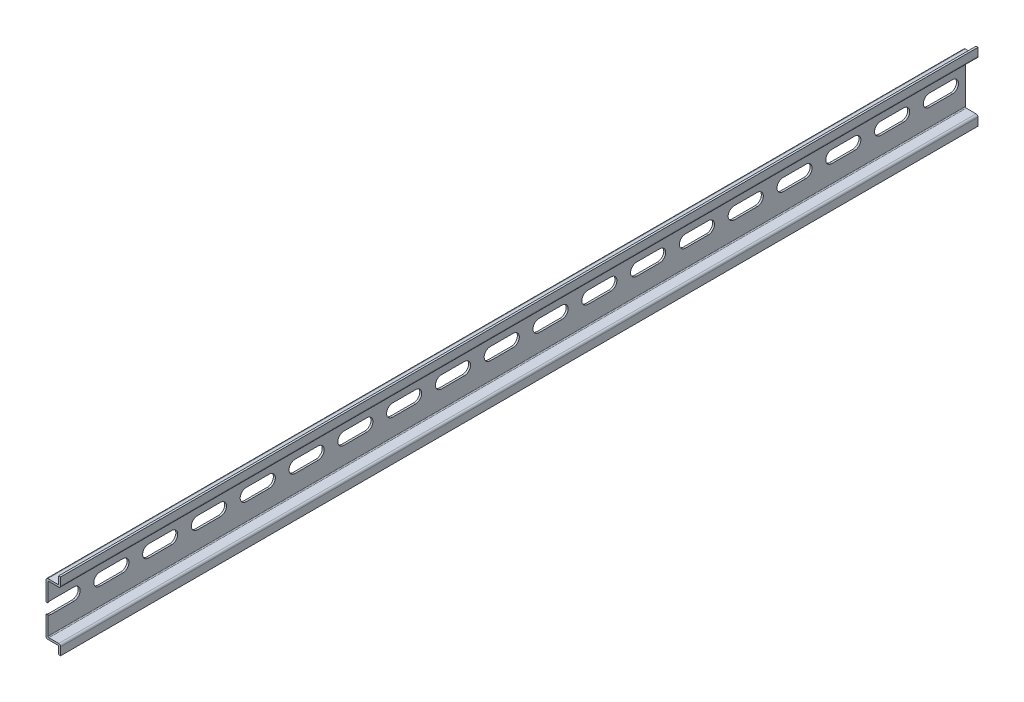
SolidWorks part; units mm, degrees
ref_plane "Front Plane" through (0, 0, 0) normal (0, 0, 1) x (1, 0, 0)
ref_plane "Top Plane" through (0, 0, 0) normal (0, 1, 0) x (1, 0, 0)
ref_plane "Right Plane" through (0, 0, 0) normal (1, 0, 0) x (0, 0, -1)
sketch "Sketch1" plane through (0, 0, 0) normal (0, 0, 1) x (1, 0, 0)
  line L0 (0, 0) -> (7.5, 0) construction
  line L1 (0, 17.5) -> (7.5, 17.5) construction
  line L2 (0, 17.5) -> (0, -17.5) construction
  line L3 (0, -17.5) -> (7.5, -17.5) construction
  line L4 (7.5, 17.5) -> (7.5, -17.5) construction
  line L5 (7.5, 17.5) -> (6.5, 17.5)
  line L6 (6.5, 17.5) -> (6.5, 14)
  line L7 (6, 13.5) -> (1, 13.5)
  line L8 (0, 12.5) -> (0, -12.5)
  line L9 (7.5, 17.5) -> (7.5, 13.5)
  line L10 (6.5, 12.5) -> (1.5, 12.5)
  line L11 (1, 12) -> (1, -12)
  line L12 (6.5, -12.5) -> (1.5, -12.5)
  line L13 (7.5, -17.5) -> (7.5, -13.5)
  line L14 (6, -13.5) -> (1, -13.5)
  line L15 (6.5, -17.5) -> (6.5, -14)
  line L16 (7.5, -17.5) -> (6.5, -17.5)
  line L17 (6.3536, 13.6464) -> (7.2071, 12.7929) construction
  line L18 (1.1464, 12.3536) -> (0.2929, 13.2071) construction
  arc A0 (1.5, 12.5) -> (1, 12) centre (1.5, 12) ccw
  arc A1 (1, 13.5) -> (0, 12.5) centre (1, 12.5) ccw
  arc A2 (7.5, 13.5) -> (6.5, 12.5) centre (6.5, 13.5) cw
  arc A3 (6, 13.5) -> (6.5, 14) centre (6, 14) ccw
  arc A4 (1, -13.5) -> (0, -12.5) centre (1, -12.5) cw
  arc A5 (1.5, -12.5) -> (1, -12) centre (1.5, -12) cw
  arc A6 (7.5, -13.5) -> (6.5, -12.5) centre (6.5, -13.5) ccw
  arc A7 (6, -13.5) -> (6.5, -14) centre (6, -14) cw
  dimension "D5" = 1
  dimension "D6" = 0.5
  dimension "D1" = 35
  dimension "D2" = 7.5
  dimension "D3" = 1
  dimension "D4" = 27
extrude "Boss-Extrude1" add sketch "Sketch1" along normal mid plane 1000
sketch "Sketch2" plane through (0, 0, 0) normal (1, 0, 0) x (0, 0, -1)
  line L0 (-493.35, 0) -> (-481.65, 0) construction
  line L1 (-493.35, 3.15) -> (-481.65, 3.15)
  line L2 (-493.35, -3.15) -> (-481.65, -3.15)
  line L3 (-487.5, 0) -> (-500, 0) construction
  line L4 (-500, 12.5) -> (-500, -12.5) construction
  line L5 (-487.5, 0) -> (-462.5, 0) construction
  line L6 (-462.5, 0) -> (-437.5, 0) construction
  arc A0 (-493.35, 3.15) -> (-493.35, -3.15) centre (-493.35, 0) ccw
  arc A1 (-481.65, -3.15) -> (-481.65, 3.15) centre (-481.65, 0) ccw
  point P2 (-487.5, 0)
  dimension "D1" = 6.3
  dimension "D2" = 18
  dimension "D4" = 12.5
  dimension "D3" = 25
extrude "Cut-Extrude1" cut sketch "Sketch2" along normal up to vertex (7.5 mm away) up to point (7.5, 0, 0)
pattern_linear "LPattern1" count 40 spacing 25 along (0, 0, -1) of "Cut-Extrude1"
sketch "Sketch3" plane through (0, 0, 500) normal (0, 0, 1) x (1, 0, 0)
  line L0 (0, 12.5) -> (0, -12.5) construction
  line L1 (29.7114, -44.0793) -> (-29.7114, -44.0793)
  line L2 (29.7114, -44.0793) -> (29.7114, 44.0793)
  line L3 (29.7114, 44.0793) -> (-29.7114, 44.0793)
  line L4 (-29.7114, -44.0793) -> (-29.7114, 44.0793)
  line L5 (29.7114, -44.0793) -> (-29.7114, 44.0793) construction
  line L6 (29.7114, 44.0793) -> (-29.7114, -44.0793) construction
  point P0 (0, 0)
extrude "Cut-Extrude2" cut sketch "Sketch3" against normal offset from surface (530 mm away) 470 up to face at (4.4, 0, -500)
equation "\"D4@Sketch2\" = \"D3@Sketch2\" / 2"
equation "\"D3@LPattern1\" = \"D3@Sketch2\""
equation "\"D1@LPattern1\" = \"D1@Boss-Extrude1\" / \"D3@LPattern1\""
